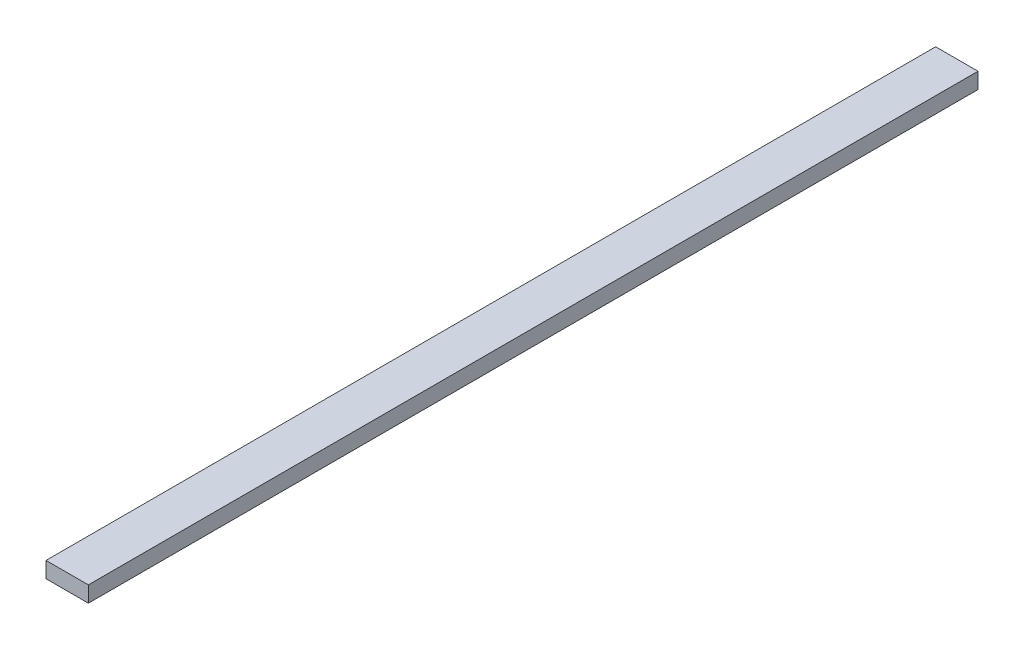
SolidWorks part; units mm, degrees
ref_plane "Front Plane" through (0, 0, 0) normal (0, 0, 1) x (1, 0, 0)
ref_plane "Top Plane" through (0, 0, 0) normal (0, 1, 0) x (1, 0, 0)
ref_plane "Right Plane" through (0, 0, 0) normal (1, 0, 0) x (0, 0, -1)
sketch "Sketch1" plane through (0, 0, 0) normal (0, 1, 0) x (1, 0, 0)
  line L1 (-25.4, -533.4) -> (25.4, -533.4)
  line L2 (-25.4, -533.4) -> (-25.4, 533.4)
  line L3 (-25.4, 533.4) -> (25.4, 533.4)
  line L4 (25.4, -533.4) -> (25.4, 533.4)
  line L5 (-25.4, -533.4) -> (25.4, 533.4) construction
  line L6 (-25.4, 533.4) -> (25.4, -533.4) construction
  point P0 (0, 0)
  dimension "D1" = 1066.8
  dimension "D2" = 50.8
extrude "Boss-Extrude1" add sketch "Sketch1" along normal blind 19.05
